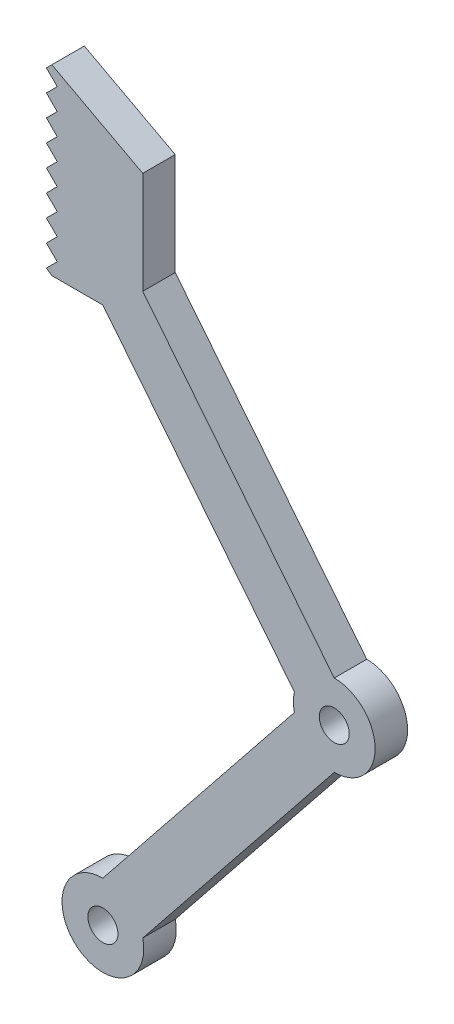
SolidWorks part; units mm, degrees
ref_plane "Front Plane" through (0, 0, 0) normal (0, 0, 1) x (1, 0, 0)
ref_plane "Top Plane" through (0, 0, 0) normal (0, 1, 0) x (1, 0, 0)
ref_plane "Right Plane" through (0, 0, 0) normal (1, 0, 0) x (0, 0, -1)
sketch "Sketch1" plane through (0, 0, 0) normal (0, 0, 1) x (1, 0, 0)
  line L0 (0, 0) -> (0, 4) construction
  line L1 (0, 4) -> (3.9031, 0.875) construction
  line L2 (0, 0) -> (1.9516, 2.4375) construction
  line L3 (1.9516, 2.4375) -> (22.6531, 28.2937) construction
  line L4 (0, 4) -> (18.75, 27.4187)
  line L5 (3.9031, 0.875) -> (22.6531, 24.2937)
  line L11 (18.75, 29.1687) -> (0, 52.5875)
  line L12 (22.6531, 32.2937) -> (3.9031, 55.7125)
  line L13 (18.75, 29.1687) -> (22.6531, 32.2937) construction
  line L14 (22.6531, 28.2937) -> (20.7016, 30.7312) construction
  line L15 (20.7016, 30.7312) -> (19.3098, 32.4695) construction
  line L19 (-5, 2.5) -> (-5, -87.5) construction
  line L20 (-12.5, 2.5) -> (2.5, 2.5) construction
  line L21 (-42.5, -87.5) -> (32.5, -87.5) construction
  line L22 (-5, 2.5) -> (-5, 52.5875) construction
  line L32 (0, 52.5875) -> (-5, 52.5875)
  line L55 (3.9031, 55.7125) -> (3.9031, 65.7125)
  line L56 (-5, 52.5875) -> (-5, 89.8812) construction
  line L57 (-5, 52.5875) -> (-5.5303, 52.9653)
  line L58 (-5.5303, 52.9653) -> (-4.4697, 54.0259)
  line L59 (-4.4697, 54.0259) -> (-5.5303, 55.0866)
  line L60 (-5.5303, 55.0866) -> (-4.4697, 56.1473)
  line L61 (-4.4697, 56.1473) -> (-5.5303, 57.2079)
  line L62 (-5.5303, 57.2079) -> (-4.4697, 58.2686)
  line L63 (-4.4697, 58.2686) -> (-5.5303, 59.3292)
  line L64 (-5.5303, 59.3292) -> (-4.4697, 60.3899)
  line L65 (-4.4697, 60.3899) -> (-5.5303, 61.4506)
  line L66 (-5.5303, 61.4506) -> (-4.4697, 62.5112)
  line L67 (-4.4697, 62.5112) -> (-5.5303, 63.5719)
  line L68 (-5.5303, 63.5719) -> (-4.4697, 64.6325)
  line L69 (-4.4697, 64.6325) -> (-5.5303, 65.6932)
  line L70 (-5.5303, 65.6932) -> (-4.4697, 66.7539)
  line L71 (-4.4697, 66.7539) -> (-5.5303, 67.8145)
  line L72 (-5.5303, 67.8145) -> (-4.4697, 68.8752)
  line L73 (-4.4697, 68.8752) -> (-5.5303, 69.9358)
  line L74 (-5.5303, 69.9358) -> (-5, 70.4674)
  line L75 (-5, 70.4674) -> (3.9031, 65.7125)
  arc A0 (0, 4) -> (3.9031, 0.875) centre (0, 0) ccw
  arc A1 (22.6531, 24.2937) -> (22.6531, 32.2937) centre (22.6531, 28.2937) ccw
  arc A2 (18.75, 27.4187) -> (18.75, 29.1687) centre (22.6531, 28.2937) cw
  dimension "D1" = 4
  dimension "D4" = 4
  dimension "D5" = 5
  dimension "D7" = 30
  dimension "D6" = 10
  dimension "D2" = 5
  dimension "D3" = 30
  dimension "D8" = 253.174
  dimension "D9" = 5
  dimension "D10" = 215.465
  dimension "D11" = 1.5
  dimension "D12" = 0.5303
  dimension "D13" = 0.5303
  dimension "D14" = 0.7509
extrude "Boss-Extrude1" add sketch "Sketch1" along normal blind 3.18
sketch "Sketch2" plane through (0, 0, 3.18) normal (0, 0, 1) x (1, 0, 0)
  circle A0 centre (22.6531, 28.2937) radius 1.47
  circle A1 centre (0, 0) radius 1.47
  dimension "D1" = 2.94
  dimension "D2" = 2.94
extrude "Cut-Extrude1" cut sketch "Sketch2" against normal through all
